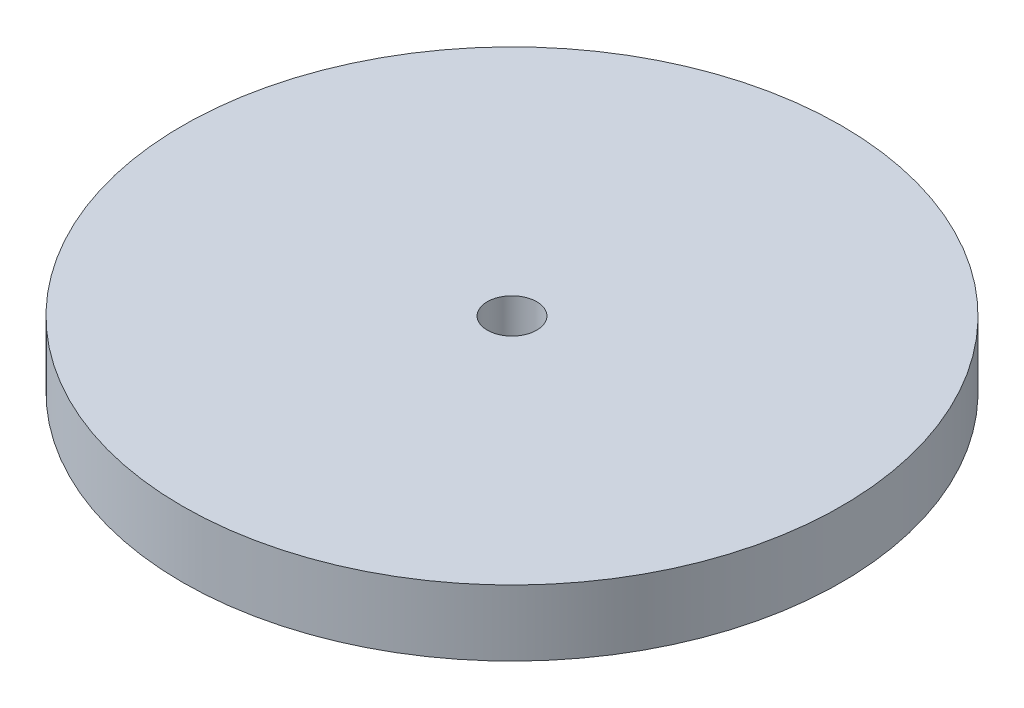
SolidWorks part; units mm, degrees
ref_plane "Front Plane" through (0, 0, 0) normal (0, 0, 1) x (1, 0, 0)
ref_plane "Top Plane" through (0, 0, 0) normal (0, 1, 0) x (1, 0, 0)
ref_plane "Right Plane" through (0, 0, 0) normal (1, 0, 0) x (0, 0, -1)
sketch "Sketch1" plane through (0, 0, 0) normal (0, 1, 0) x (1, 0, 0)
  circle A0 centre (0, 0) radius 10
  dimension "D1" = 20
extrude "Boss-Extrude1" add sketch "Sketch1" along normal blind 2
sketch "Sketch2" plane through (0, 2, 0) normal (0, 1, 0) x (1, 0, 0)
  circle A1 centre (0, 0) radius 0.75
  dimension "D1" = 1.5
extrude "Cut-Extrude1" cut sketch "Sketch2" against normal through all
